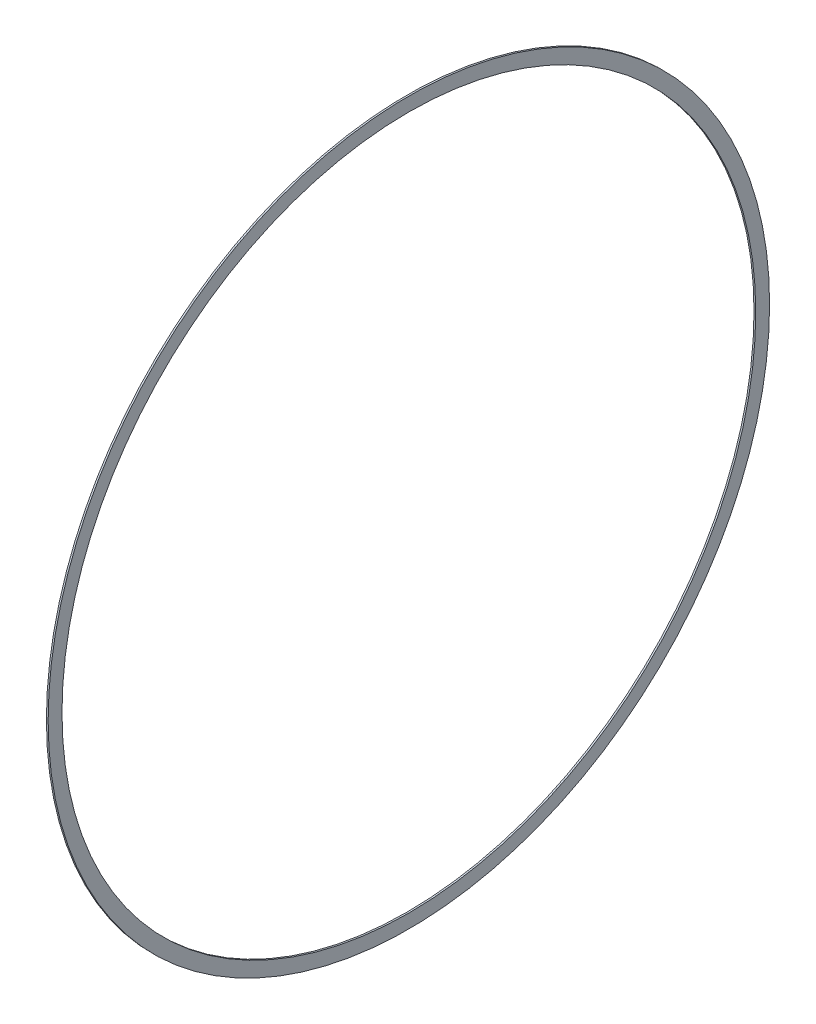
SolidWorks part; units mm, degrees
material "ASTM A36 Steel"
ref_plane "Front Plane" through (0, 0, 0) normal (0, 0, 1) x (1, 0, 0)
ref_plane "Top Plane" through (0, 0, 0) normal (0, 1, 0) x (1, 0, 0)
ref_plane "Right Plane" through (0, 0, 0) normal (1, 0, 0) x (0, 0, -1)
sketch "Sketch1" plane through (0, 0, 0) normal (1, 0, 0) x (0, 0, -1)
  circle A0 centre (0, 0) radius 1042
  circle A1 centre (0, 0) radius 1002
  dimension "D1" = 2084
  dimension "D2" = 40
extrude "Boss-Extrude1" add sketch "Sketch1" along normal blind 5
